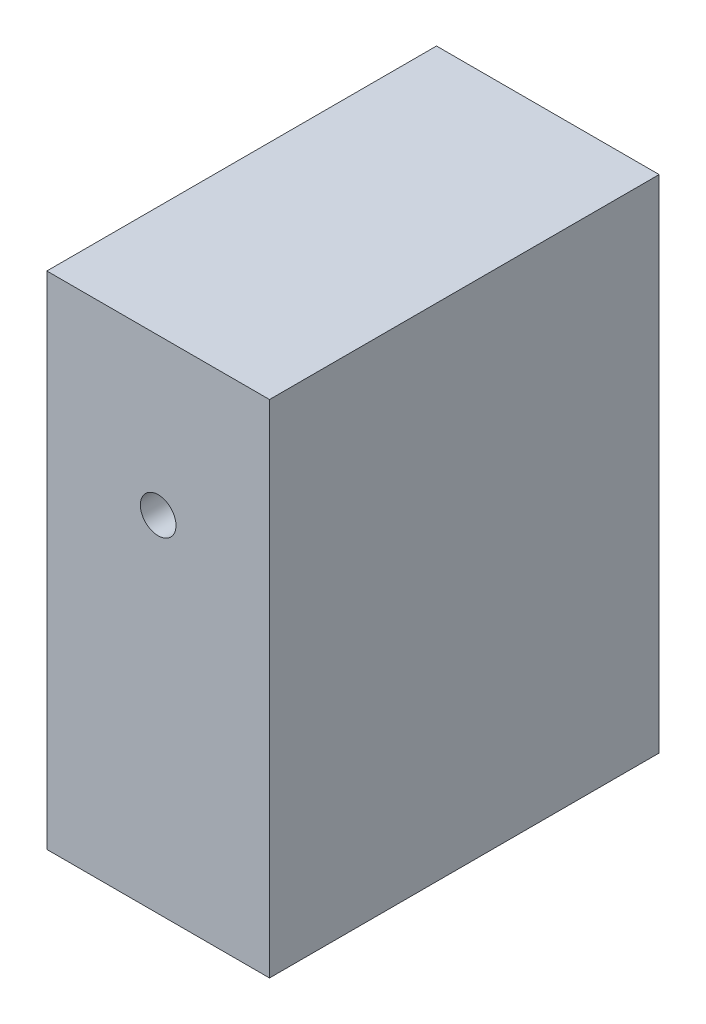
SolidWorks part; units mm, degrees
ref_plane "前基準面" through (0, 0, 0) normal (0, 0, 1) x (1, 0, 0)
ref_plane "上基準面" through (0, 0, 0) normal (0, 1, 0) x (1, 0, 0)
ref_plane "右基準面" through (0, 0, 0) normal (1, 0, 0) x (0, 0, -1)
sketch "草圖1" plane through (0, 0, 0) normal (0, 0, 1) x (1, 0, 0)
  line L1 (-51.7647, 52.9412) -> (-31.7647, 52.9412)
  line L2 (-51.7647, 52.9412) -> (-51.7647, 7.9412)
  line L3 (-51.7647, 7.9412) -> (-31.7647, 7.9412)
  line L4 (-31.7647, 52.9412) -> (-31.7647, 7.9412)
  circle A0 centre (-41.7647, 38.9412) radius 1.6
  dimension "D3" = 3.2
  dimension "D1" = 20
  dimension "D2" = 45
  dimension "D4" = 31
  dimension "D5" = 10
extrude "填料-伸長1" add sketch "草圖1" along normal blind 35
